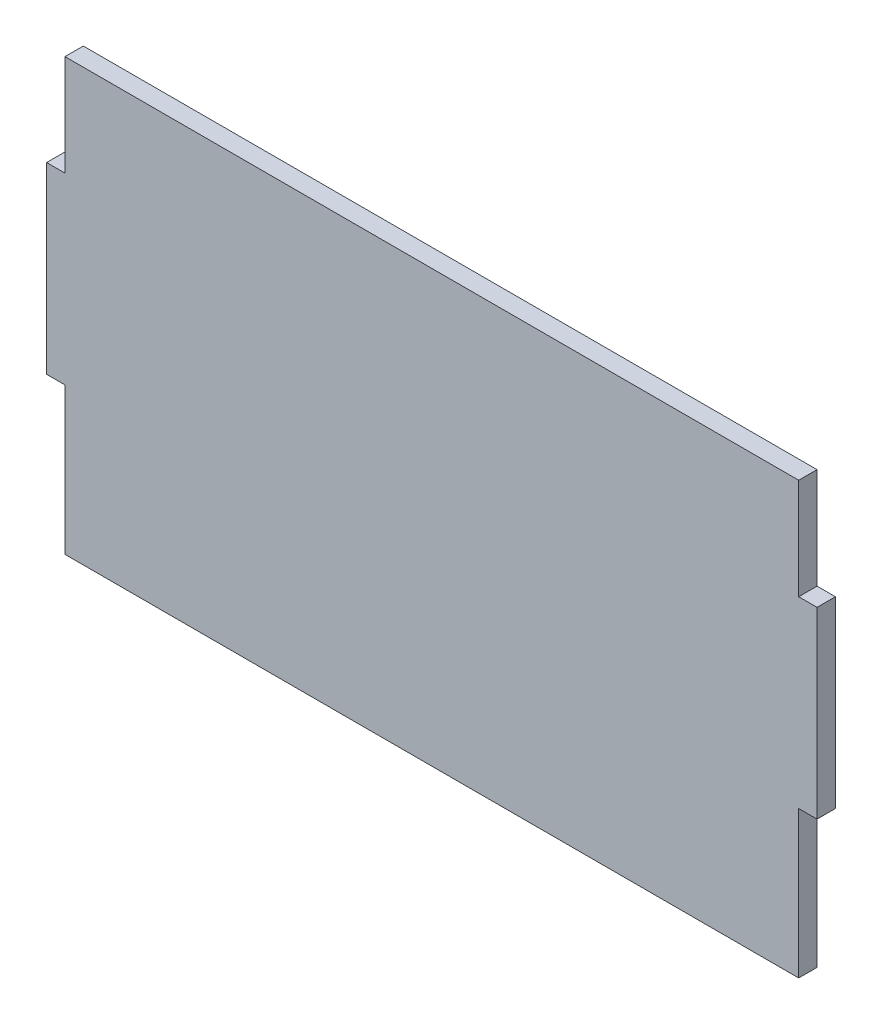
SolidWorks part; units mm, degrees
ref_plane "Спереди" through (0, 0, 0) normal (0, 0, 1) x (1, 0, 0)
ref_plane "Сверху" through (0, 0, 0) normal (0, 1, 0) x (1, 0, 0)
ref_plane "Справа" through (0, 0, 0) normal (1, 0, 0) x (0, 0, -1)
sketch "Эскиз1" plane through (0, 0, 0) normal (0, 0, 1) x (1, 0, 0)
  line L1 (0, 0) -> (80, 0)
  line L2 (0, 0) -> (0, 47)
  line L3 (0, 47) -> (80, 47)
  line L4 (80, 0) -> (80, 47)
  line L5 (80, 36) -> (82, 36)
  line L6 (80, 36) -> (80, 16)
  line L7 (80, 16) -> (82, 16)
  line L8 (82, 36) -> (82, 16)
  line L9 (0, 36) -> (-2, 36)
  line L10 (0, 36) -> (0, 16)
  line L11 (0, 16) -> (-2, 16)
  line L12 (-2, 36) -> (-2, 16)
  point P15 (0, 23.5)
  dimension "D1" = 80
  dimension "D2" = 47
  dimension "D3" = 11
  dimension "D4" = 11
  dimension "D5" = 20
  dimension "D6" = 20
  dimension "D7" = 2
  dimension "D8" = 2
extrude "Бобышка-Вытянуть1" add sketch "Эскиз1" along normal blind 2 contours L8 L5 L4 L7 | L1 L4 L3 L2 | L12 L11 L10 L9
